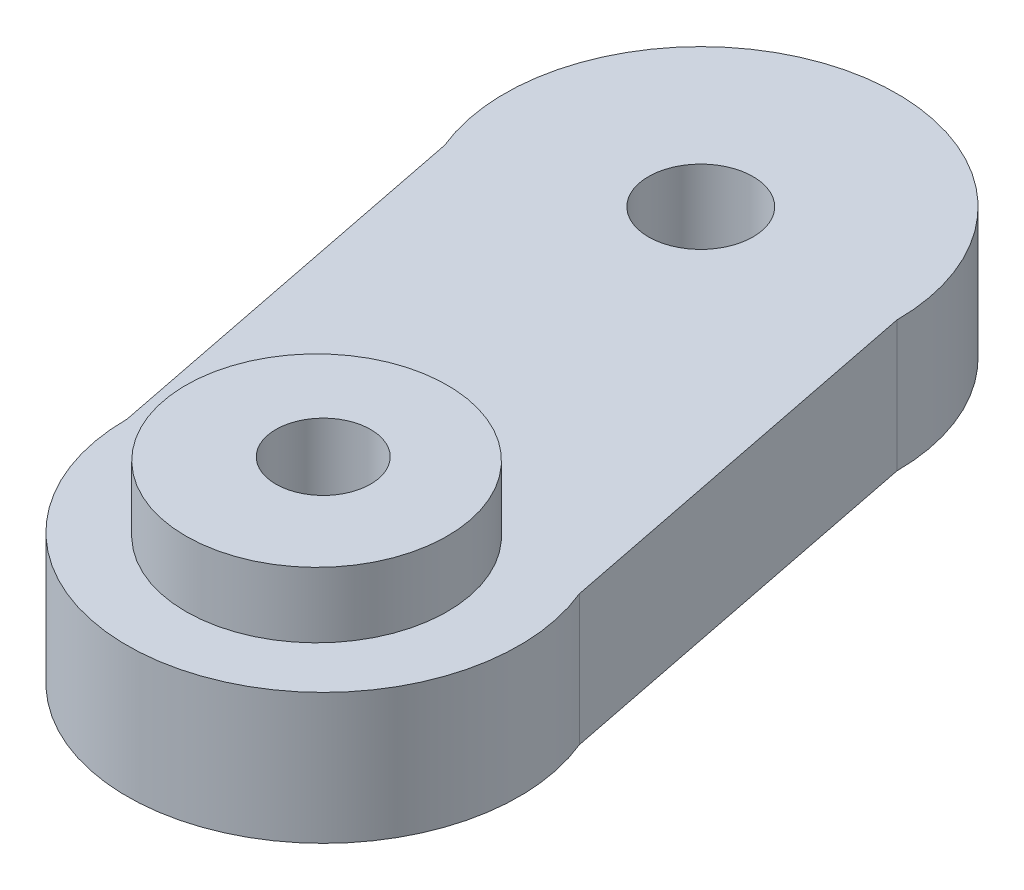
SolidWorks part; units mm, degrees
ref_plane "Front Plane" through (0, 0, 0) normal (0, 0, 1) x (1, 0, 0)
ref_plane "Top Plane" through (0, 0, 0) normal (0, 1, 0) x (1, 0, 0)
ref_plane "Right Plane" through (0, 0, 0) normal (1, 0, 0) x (0, 0, -1)
sketch "Sketch1" plane through (0, 0, 0) normal (0, 1, 0) x (1, 0, 0)
  line L0 (-5.5477, -2.2855) -> (-3.15, -14.4)
  line L1 (0, 0) -> (157.7, 0) construction
  line L2 (0, 0) -> (0, -110.8) construction
  line L3 (0, -110.8) -> (157.7, -110.8) construction
  line L4 (157.7, 0) -> (157.7, -110.8) construction
  line L5 (2.85, -14.4) -> (154.85, -14.4) construction
  line L6 (2.85, -14.4) -> (2.85, -96.4) construction
  line L7 (2.85, -96.4) -> (154.85, -96.4) construction
  line L8 (154.85, -14.4) -> (154.85, -96.4) construction
  line L9 (8.3977, -12.1145) -> (6, 0)
  arc A0 (-3.15, -14.4) -> (8.3977, -12.1145) centre (2.85, -14.4) ccw
  arc A1 (6, 0) -> (-5.5477, -2.2855) centre (0, 0) ccw
  circle A2 centre (0, 0) radius 1.6
  circle A3 centre (2.85, -14.4) radius 1.45
  dimension "D7" = 12
  dimension "D8" = 12
  dimension "D9" = 3.2
  dimension "D10" = 2.9
  dimension "D1" = 110.8
  dimension "D2" = 157.7
  dimension "D3" = 82
  dimension "D4" = 152
  dimension "D5" = 2.85
  dimension "D6" = 14.4
extrude "Boss-Extrude1" add sketch "Sketch1" along normal blind 4
sketch "Sketch2" plane through (0, 4, 0) normal (0, 1, 0) x (1, 0, 0)
  circle A0 centre (2.85, -14.4) radius 1.45
  circle A1 centre (2.85, -14.6026) radius 4
  dimension "D1" = 8
extrude "Boss-Extrude2" add sketch "Sketch2" along normal blind 2
equation "\"D5@Sketch1\"=(\"D2@Sketch1\"-\"D4@Sketch1\")/2"
equation "\"D6@Sketch1\"=(\"D1@Sketch1\"-\"D3@Sketch1\")/2"
